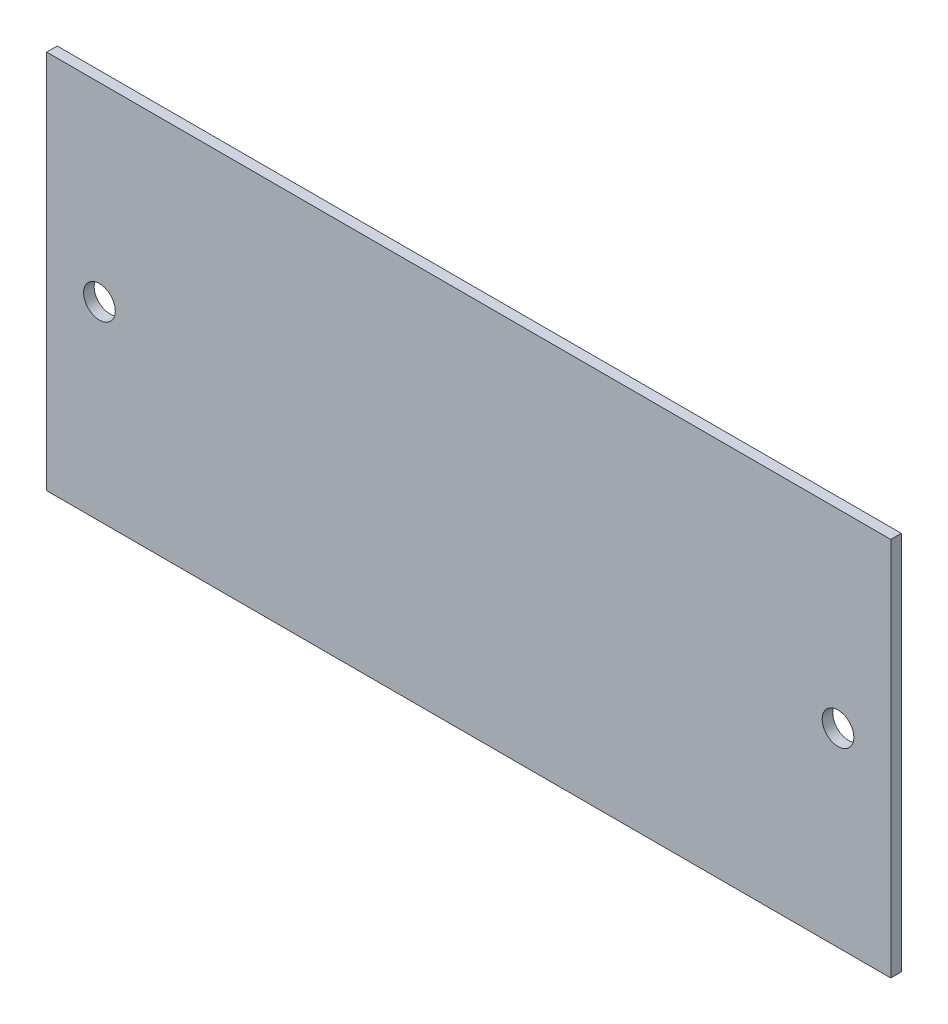
SolidWorks part; units mm, degrees
material "PLA"
ref_plane "Front Plane" through (0, 0, 0) normal (0, 0, 1) x (1, 0, 0)
ref_plane "Top Plane" through (0, 0, 0) normal (0, 1, 0) x (1, 0, 0)
ref_plane "Right Plane" through (0, 0, 0) normal (1, 0, 0) x (0, 0, -1)
sketch "Sketch1" plane through (0, 0, 0) normal (0, 0, 1) x (1, 0, 0)
  line L0 (0, 0) -> (101.6, 0)
  line L1 (0, 0) -> (0, 45.72)
  line L2 (0, 45.72) -> (101.6, 45.72)
  line L3 (101.6, 0) -> (101.6, 45.72)
  dimension "D1" = 45.72
  dimension "D2" = 101.6
extrude "Base Extrude" add sketch "Sketch1" along normal blind 1.27
sketch "Sketch2" plane through (0, 0, 1.27) normal (0, 0, 1) x (1, 0, 0)
  line L0 (50.8, 45.72) -> (50.8, 0) construction
  line L1 (101.6, 45.72) -> (0, 45.72) construction
  line L2 (0, 0) -> (101.6, 0) construction
  line L4 (0, 45.72) -> (0, 0) construction
  line L5 (0, 22.86) -> (101.6, 22.86) construction
  line L6 (101.6, 0) -> (101.6, 45.72) construction
  circle A0 centre (6.35, 22.86) radius 1.905
  circle A2 centre (95.25, 22.86) radius 1.905
  dimension "D1" = 6.35
  dimension "D2" = 3.81
extrude "Hole Cut" cut sketch "Sketch2" against normal up to next
